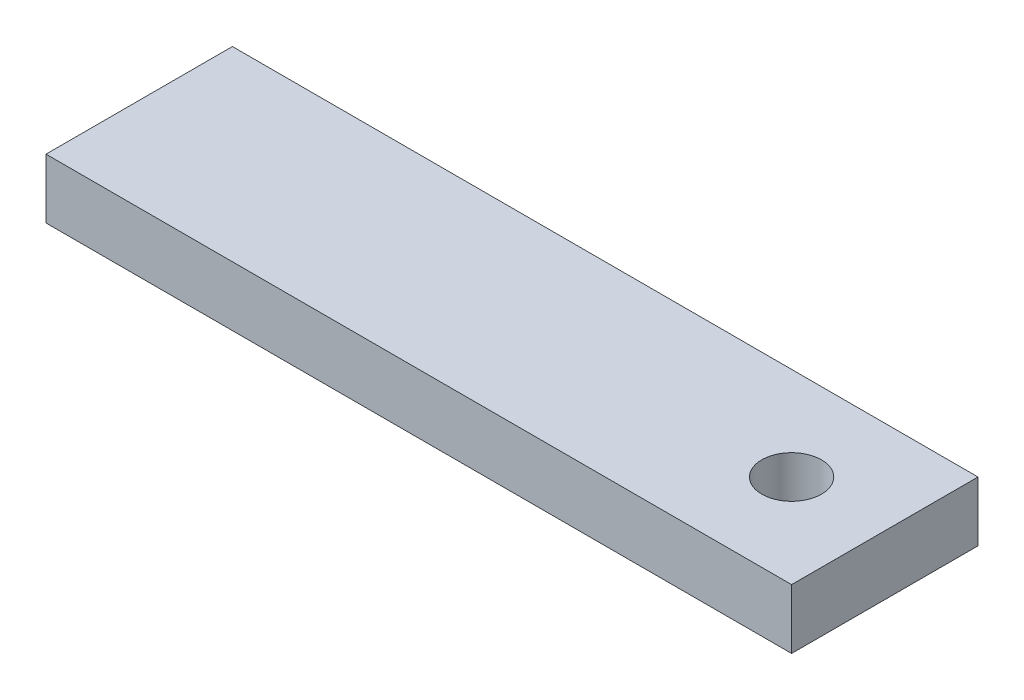
SolidWorks part; units mm, degrees
ref_plane "Front Plane" through (0, 0, 0) normal (0, 0, 1) x (1, 0, 0)
ref_plane "Top Plane" through (0, 0, 0) normal (0, 1, 0) x (1, 0, 0)
ref_plane "Right Plane" through (0, 0, 0) normal (1, 0, 0) x (0, 0, -1)
sketch "Sketch1" plane through (0, 0, 0) normal (0, 1, 0) x (1, 0, 0)
  line L1 (-50, 12.5) -> (50, 12.5)
  line L2 (-50, 12.5) -> (-50, -12.5)
  line L3 (-50, -12.5) -> (50, -12.5)
  line L4 (50, 12.5) -> (50, -12.5)
  line L5 (-50, 12.5) -> (50, -12.5) construction
  line L6 (-50, -12.5) -> (50, 12.5) construction
  circle A0 centre (37.5, 0) radius 4
  point P0 (0, 0)
  dimension "D3" = 8
  dimension "D4" = 12.5
  dimension "D5" = 12.5
  dimension "D1" = 25
  dimension "D2" = 100
extrude "Boss-Extrude1" add sketch "Sketch1" along normal blind 8
